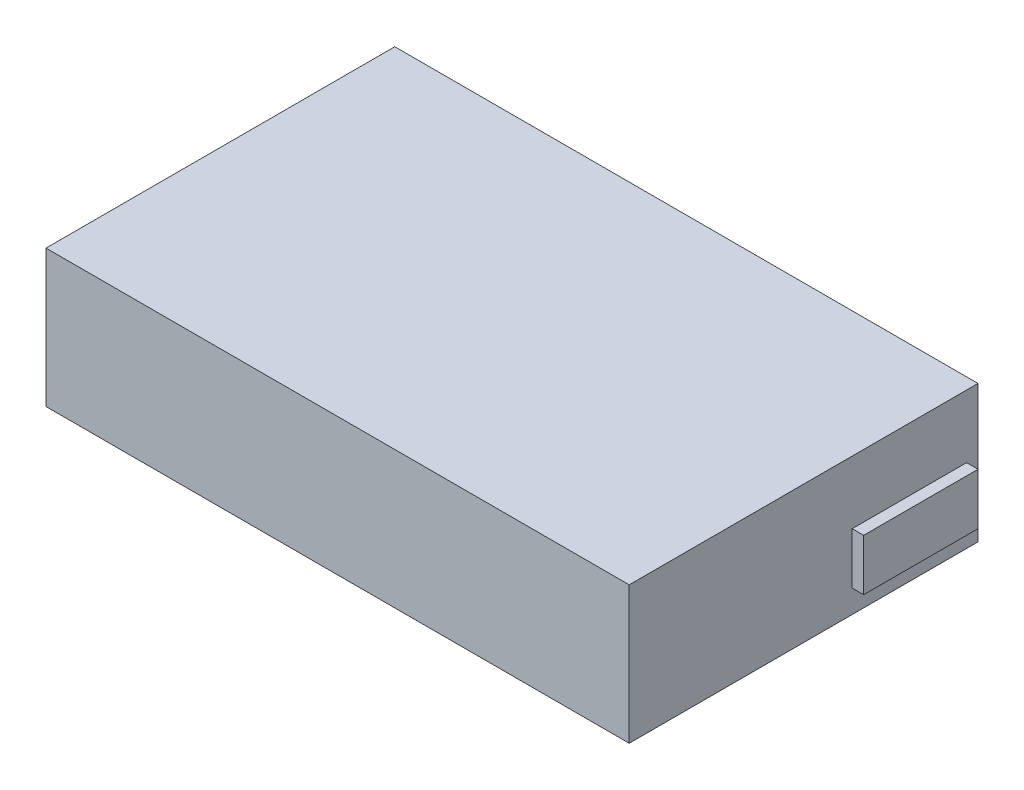
SolidWorks part; units mm, degrees
ref_plane "Alzado" through (0, 0, 0) normal (0, 0, 1) x (1, 0, 0)
ref_plane "Planta" through (0, 0, 0) normal (0, 1, 0) x (1, 0, 0)
ref_plane "Vista lateral" through (0, 0, 0) normal (1, 0, 0) x (0, 0, -1)
sketch "Croquis1" plane through (0, 0, 0) normal (0, 1, 0) x (1, 0, 0)
  line L1 (-51, -30.5) -> (51, -30.5)
  line L2 (-51, -30.5) -> (-51, 30.5)
  line L3 (-51, 30.5) -> (51, 30.5)
  line L4 (51, -30.5) -> (51, 30.5)
  line L5 (-51, -30.5) -> (51, 30.5) construction
  line L6 (-51, 30.5) -> (51, -30.5) construction
  point P0 (0, 0)
  dimension "D1" = 102
  dimension "D2" = 61
extrude "Saliente-Extruir1" add sketch "Croquis1" along normal blind 24
sketch "Croquis2" plane through (51, 0, 0) normal (1, 0, 0) x (0, 0, -1)
  line L0 (-30.5, 0) -> (30.5, 0) construction
  line L1 (8.5, 13) -> (28.5, 13)
  line L2 (8.5, 13) -> (8.5, 4)
  line L3 (8.5, 4) -> (28.5, 4)
  line L4 (28.5, 13) -> (28.5, 4)
  line L5 (30.5, 24) -> (30.5, 0) construction
  dimension "D1" = 4
  dimension "D2" = 9
  dimension "D3" = 20
  dimension "D4" = 2
extrude "Saliente-Extruir2" add sketch "Croquis2" along normal blind 2
